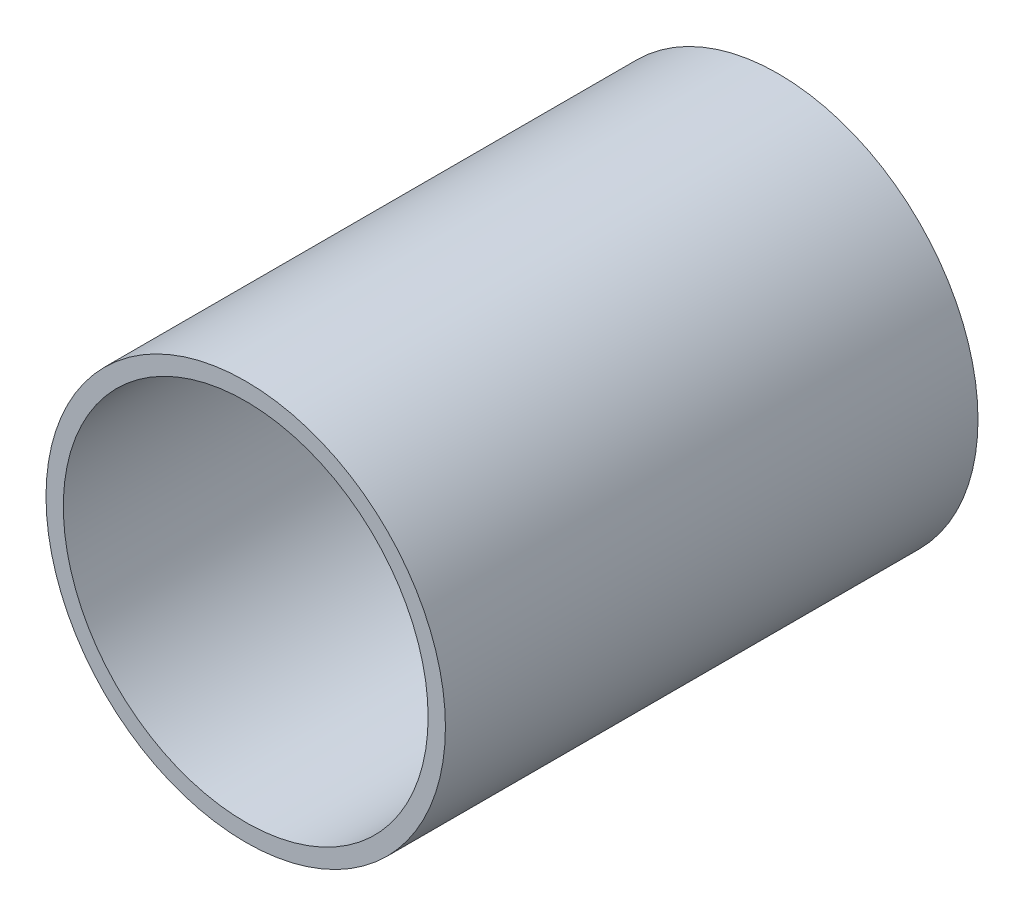
SolidWorks part; units mm, degrees
ref_plane "Front Plane" through (0, 0, 0) normal (0, 0, 1) x (1, 0, 0)
ref_plane "Top Plane" through (0, 0, 0) normal (0, 1, 0) x (1, 0, 0)
ref_plane "Right Plane" through (0, 0, 0) normal (1, 0, 0) x (0, 0, -1)
sketch "Sketch1" plane through (0, 0, 0) normal (0, 0, 1) x (1, 0, 0)
  circle A0 centre (0, 0) radius 17.399
  circle A1 centre (0, 0) radius 19.05
  dimension "D1" = 34.798
  dimension "D2" = 38.1
extrude "Boss-Extrude1" add sketch "Sketch1" along normal blind 50.8
